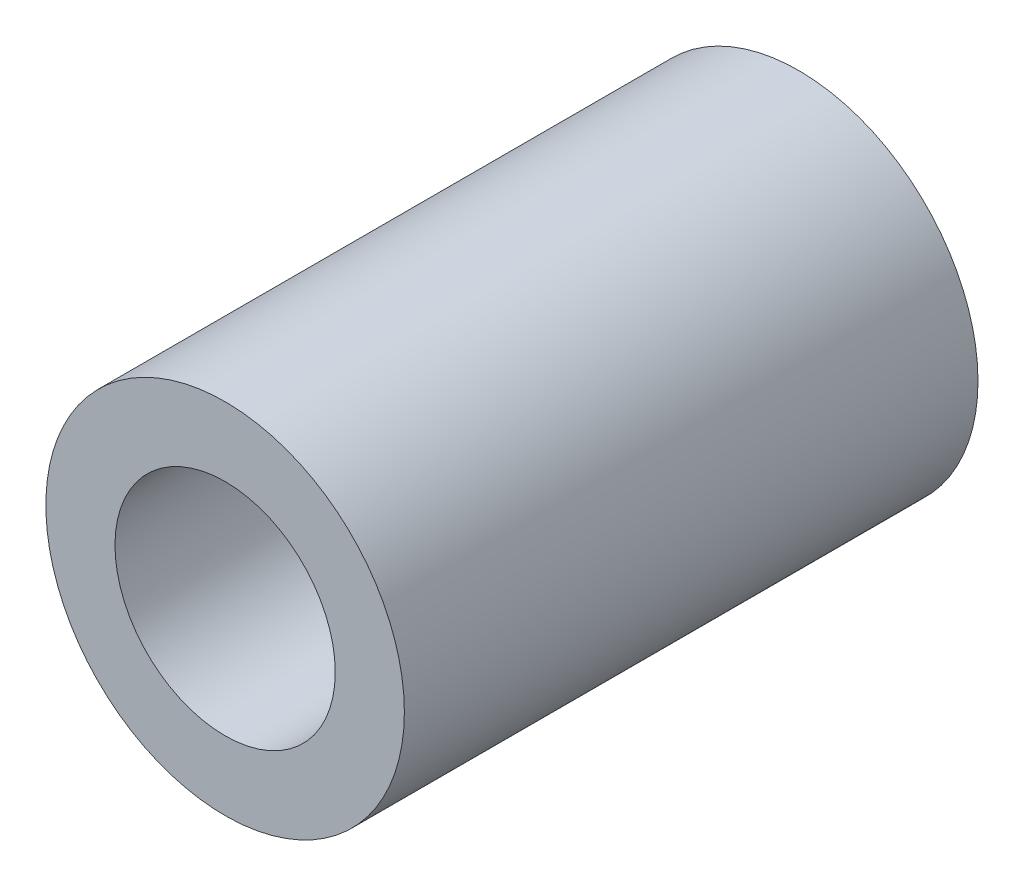
SolidWorks part; units mm, degrees
ref_plane "Front Plane" through (0, 0, 0) normal (0, 0, 1) x (1, 0, 0)
ref_plane "Top Plane" through (0, 0, 0) normal (0, 1, 0) x (1, 0, 0)
ref_plane "Right Plane" through (0, 0, 0) normal (1, 0, 0) x (0, 0, -1)
sketch "Sketch1" plane through (0, 0, 0) normal (0, 0, 1) x (1, 0, 0)
  circle A0 centre (0, 0) radius 3.9688
  circle A1 centre (0, 0) radius 2.4384
  dimension "OD" = 7.9375
  dimension "ID" = 4.8768
extrude "Extrude1" add sketch "Sketch1" along normal mid plane 12.7
sketch "Sketch2" plane through (0, 0, 0) normal (1, 0, 0) x (0, 0, -1)
  line L0 (-6.35, -2.4384) -> (6.35, -2.4384) construction
  line L3 (6.35, 2.4384) -> (-6.35, 2.4384) construction
  line L5 (-6.35, -2.4384) -> (6.35, -2.4384)
  line L6 (6.35, 2.4384) -> (-6.35, 2.4384)
sketch "Sketch4" plane through (0, 0, 6.35) normal (0, 0, 1) x (1, 0, 0)
  line L0 (0, 0) -> (-1.7242, 1.7242)
  line L1 (0, -2.1828) -> (0, 2.1828) construction
  circle A0 centre (0, 0) radius 2.4384 construction
  dimension "D1" = 45
